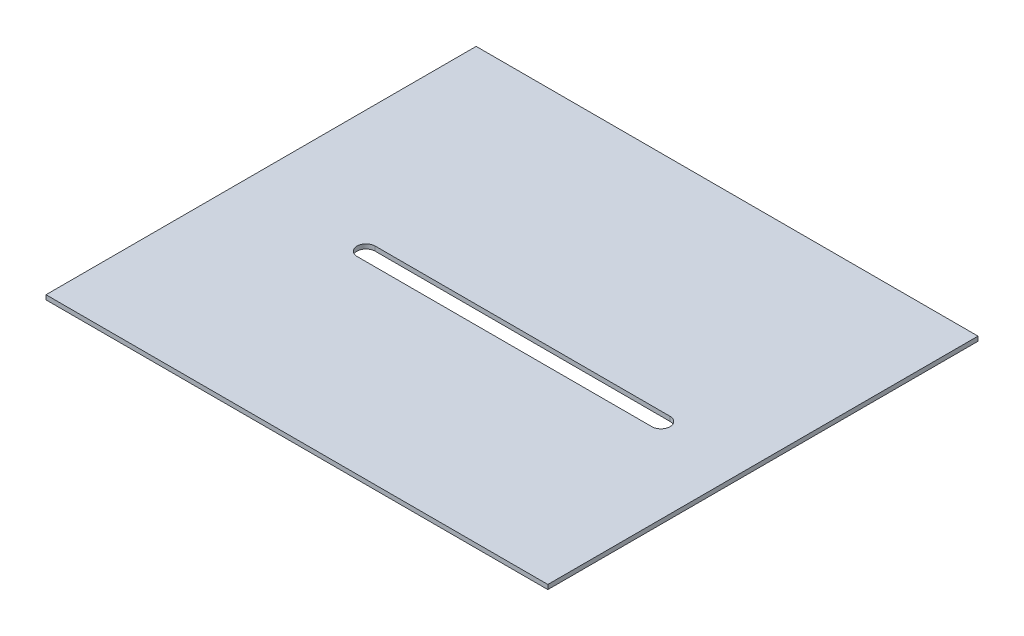
SolidWorks part; units mm, degrees
ref_plane "Front Plane" through (0, 0, 0) normal (0, 0, 1) x (1, 0, 0)
ref_plane "Top Plane" through (0, 0, 0) normal (0, 1, 0) x (1, 0, 0)
ref_plane "Right Plane" through (0, 0, 0) normal (1, 0, 0) x (0, 0, -1)
sketch "Sketch1" plane through (0, 0, 0) normal (0, 1, 0) x (1, 0, 0)
  line L0 (295.6603, 140.0901) -> (86.7174, 140.0901) construction
  line L1 (0, 0) -> (355.6, 0)
  line L2 (0, 0) -> (0, 304.8)
  line L3 (0, 304.8) -> (355.6, 304.8)
  line L4 (355.6, 0) -> (355.6, 304.8)
  line L7 (295.6603, 133.6795) -> (86.7174, 133.6795)
  line L8 (295.6603, 146.5006) -> (86.7174, 146.5006)
  arc A2 (295.6603, 133.6795) -> (295.6603, 146.5006) centre (295.6603, 140.0901) ccw
  arc A3 (86.7174, 146.5006) -> (86.7174, 133.6795) centre (86.7174, 140.0901) ccw
  point P7 (191.1888, 140.0901)
  point P12 (86.7174, 149.5507)
  point P13 (295.6603, 140.0901)
  dimension "D1" = 355.6
  dimension "D2" = 304.8
extrude "Boss-Extrude1" add sketch "Sketch1" along normal blind 3.175
